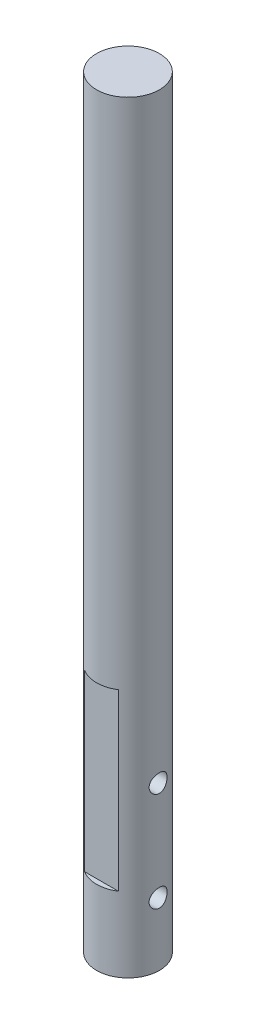
SolidWorks part; units mm, degrees
ref_plane "Спереди" through (0, 0, 0) normal (0, 0, 1) x (1, 0, 0)
ref_plane "Сверху" through (0, 0, 0) normal (0, 1, 0) x (1, 0, 0)
ref_plane "Справа" through (0, 0, 0) normal (1, 0, 0) x (0, 0, -1)
sketch "Эскиз1" plane through (0, 0, 0) normal (0, 1, 0) x (1, 0, 0)
  circle A0 centre (1.7081, -2.5635) radius 3.5
extrude "Вытянуть1" add sketch "Эскиз1" along normal blind 85 from offset 10
sketch "Эскиз2" plane through (0, 0, 0) normal (1, 0, 0) x (0, 0, -1)
  line L0 (-2.5635, 0) -> (-2.5635, -13.9082) construction
  line L2 (-5.5144, 17.7674) -> (-5.5144, -1.6803)
  line L3 (4.7459, 17.7674) -> (0.3873, 17.7674)
  line L4 (4.7459, 17.7674) -> (4.7459, -1.6803)
  line L5 (4.7459, -1.6803) -> (0.3873, -1.6803)
  line L6 (0.3873, 17.7674) -> (0.3873, -1.6803)
  line L7 (-9.8729, -1.6803) -> (-5.5144, -1.6803)
  line L8 (-9.8729, 17.7674) -> (-9.8729, -1.6803)
  line L9 (-9.8729, 17.7674) -> (-5.5144, 17.7674)
extrude "Вытянуть2" cut sketch "Эскиз2" against normal mid plane 18
sketch "Эскиз3" plane through (0, 0, 0) normal (1, 0, 0) x (0, 0, -1)
  line L0 (-2.5635, 2.6942) -> (-2.5635, 22.0862) construction
  circle A0 centre (-2.5635, -2.9801) radius 1
  circle A2 centre (-2.5635, 8.0922) radius 1
extrude "Вытянуть3" cut sketch "Эскиз3" against normal mid plane 18
